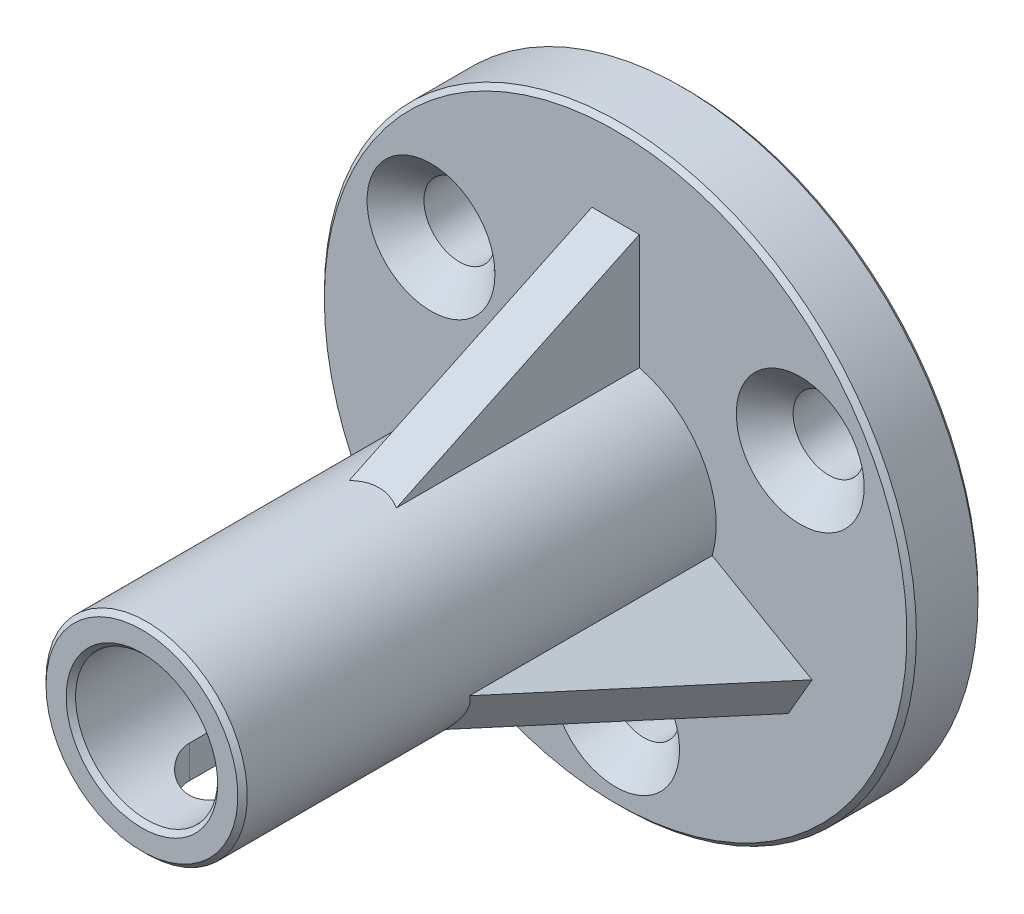
SolidWorks part; units mm, degrees
ref_plane "Front Plane" through (0, 0, 0) normal (0, 0, 1) x (1, 0, 0)
ref_plane "Top Plane" through (0, 0, 0) normal (0, 1, 0) x (1, 0, 0)
ref_plane "Right Plane" through (0, 0, 0) normal (1, 0, 0) x (0, 0, -1)
sketch "Sketch1" plane through (0, 0, 0) normal (0, 0, 1) x (1, 0, 0)
  circle A0 centre (0, 0) radius 12.5
  dimension "D1" = 25
extrude "Boss-Extrude1" add sketch "Sketch1" along normal blind 3
sketch "Sketch2" plane through (0, 0, 3) normal (0, 0, 1) x (1, 0, 0)
  circle A0 centre (0, 0) radius 4.25
  circle A1 centre (0, 0) radius 3
  dimension "D1" = 8.5
  dimension "D2" = 6
extrude "Boss-Extrude2" add sketch "Sketch2" along normal blind 20
sketch "Sketch7" plane through (0, 0, 3) normal (0, 0, 1) x (1, 0, 0)
  circle A2 centre (7.7942, 4.5) radius 1.5
  circle A3 centre (0, -9) radius 1.5
  circle A4 centre (-7.7942, 4.5) radius 1.5
  point P13 (0, 0)
  dimension "D4" = 3
  dimension "D2" = 3
extrude "Cut-Extrude2" cut sketch "Sketch7" against normal up to next
chamfer "Chamfer3" distance 1.2 angle 45 3 edges at (-6.2942, 4.5, 3) (9.2942, 4.5, 3) (1.5, -9, 3)
ref_plane "Plane2" through (0, -4.25, 0) normal (0, 1, 0) x (1, 0, 0)
sketch "Sketch9" plane through (0, -4.25, 0) normal (0, 1, 0) x (1, 0, 0)
  line L0 (-4.25, -3) -> (-4.25, -23) construction
  line L1 (4.25, -23) -> (4.25, -3) construction
  line L2 (-4.25, -23) -> (4.25, -23) construction
  line L3 (-1.5, -13.5) -> (-1.5, -19.5)
  line L4 (1.5, -13.5) -> (1.5, -19.5)
  arc A0 (-1.5, -19.5) -> (1.5, -19.5) centre (0, -19.5) ccw
  arc A1 (1.5, -13.5) -> (-1.5, -13.5) centre (0, -13.5) ccw
  dimension "D1" = 3
  dimension "D5" = 6
  dimension "D6" = 3
  dimension "D2" = 4.25
  dimension "D3" = 4.25
  dimension "D4" = 3.5
extrude "Cut-Extrude4" cut sketch "Sketch9" along normal up to next
sketch "Sketch10" plane through (0, 0, 3) normal (0, 0, 1) x (1, 0, 0)
  circle A1 centre (0, 0) radius 3
  circle A2 centre (0, 0) radius 3
  dimension "D1" = 0
extrude "Cut-Extrude5" cut sketch "Sketch10" against normal up to next
sketch "Sketch11" plane through (0, 0, 3) normal (0, 0, 1) x (1, 0, 0)
  line L1 (0, 0) -> (7.7942, -4.5)
  line L2 (0, 0) -> (-7.7942, -4.5)
  line L3 (0, 0) -> (0, 9)
  circle A0 centre (0, 0) radius 9
  point P11 (0, 0)
  dimension "D1" = 18
  dimension "D3" = 3
sketch "Sketch13" plane through (0, 0, 0) normal (1, 0, 0) x (0, 0, -1)
  line L0 (-3, 9) -> (-13, 4.25)
  line L1 (-3, 0) -> (-3, 9) construction
  line L2 (-3, 4.25) -> (-23, 4.25) construction
  dimension "D1" = 10
rib "Rib3" sketch "Sketch13" sketch "Sketch13" thickness 2 extrusion direction parallel to sketch draft on no parameters "D1"=2
pattern_circular "CirPattern3" count 3 every 120 about axis through (0, 0, 0) along (0, 0, 1) of "Rib3"
chamfer "Chamfer8" distance 0.2 angle 45 4 edges at (12.5, 0, 0) (12.5, 0, 3) (4.25, 0, 23) (3, 0, 23)
